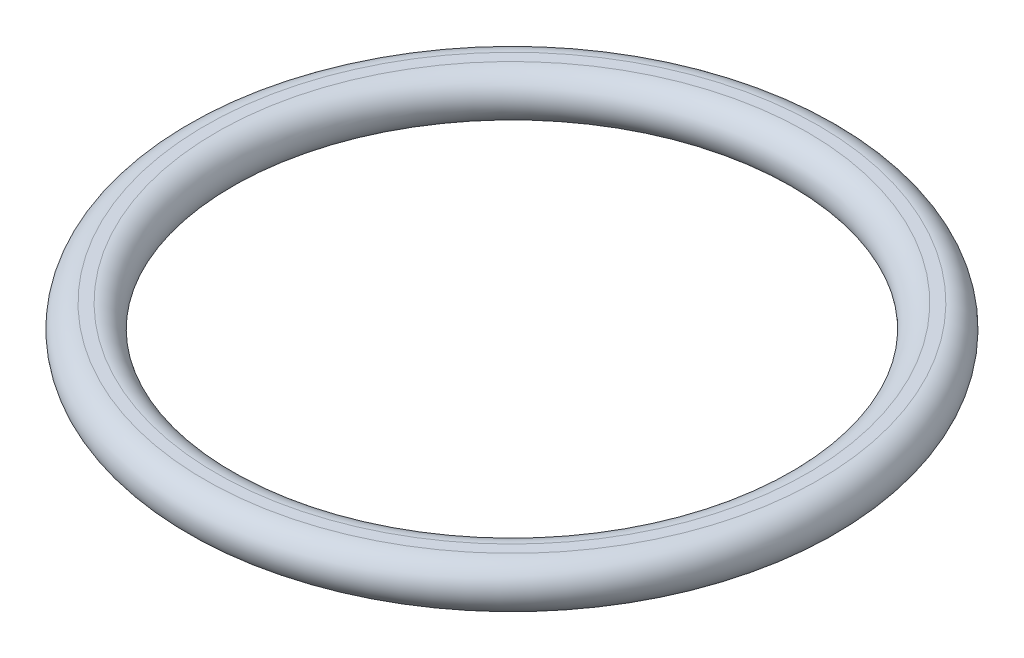
SolidWorks part; units mm, degrees
material "NEOPRENE"
ref_plane "Front Plane" through (0, 0, 0) normal (0, 0, 1) x (1, 0, 0)
ref_plane "Top Plane" through (0, 0, 0) normal (0, 1, 0) x (1, 0, 0)
ref_plane "Right Plane" through (0, 0, 0) normal (1, 0, 0) x (0, 0, -1)
sketch "Sketch1" plane through (0, 0, 0) normal (0, 0, 1) x (1, 0, 0)
  line L0 (0, 0) -> (0, 31.3765) construction
  line L1 (20.6375, 0) -> (21.4313, 0) construction
  line L2 (20.6375, 1.5875) -> (21.4313, 1.5875)
  line L3 (20.6375, -1.5875) -> (21.4313, -1.5875)
  line L4 (21.0344, 0) -> (19.05, 0)
  arc A0 (20.6375, 1.5875) -> (20.6375, -1.5875) centre (20.6375, 0) ccw
  arc A1 (21.4313, -1.5875) -> (21.4313, 1.5875) centre (21.4313, 0) ccw
  point P5 (21.0344, 0)
  dimension "D1" = 3.175
  dimension "D2" = 0.7937
  dimension "D3" = 19.05
revolve "Revolve1" add sketch "Sketch1" angle 360 about L0
